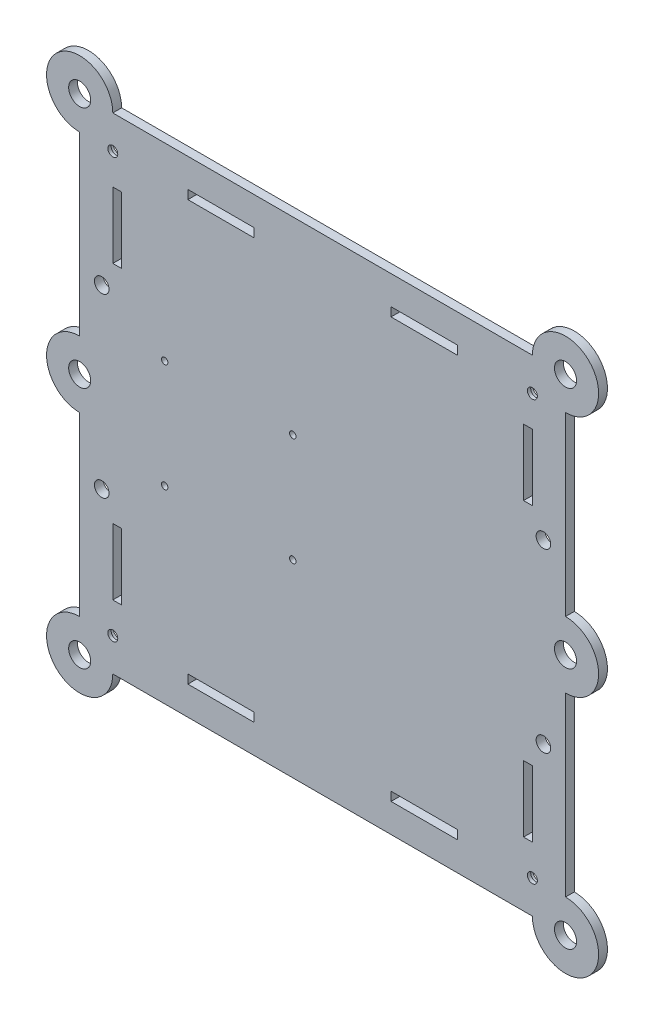
SolidWorks part; units mm, degrees
material "Aleación 6061"
ref_plane "Alzado" through (0, 0, 0) normal (0, 0, 1) x (1, 0, 0)
ref_plane "Planta" through (0, 0, 0) normal (0, 1, 0) x (1, 0, 0)
ref_plane "Vista lateral" through (0, 0, 0) normal (1, 0, 0) x (0, 0, -1)
sketch "Sk_Fondo" plane through (0, 0, 0) normal (0, 0, 1) x (1, 0, 0)
  line L0 (-110, 15) -> (-110, 95)
  line L1 (-95, -110) -> (95, -110)
  line L2 (-110, -95) -> (-110, -15)
  line L3 (-95, 110) -> (95, 110)
  line L4 (110, -95) -> (110, -15)
  line L5 (-110, -110) -> (110, 110) construction
  line L6 (-110, 110) -> (110, -110) construction
  line L7 (110, 15) -> (110, 95)
  arc A0 (-95, 110) -> (-110, 95) centre (-110, 110) ccw
  arc A1 (110, 95) -> (95, 110) centre (110, 110) ccw
  arc A2 (-110, -95) -> (-95, -110) centre (-110, -110) ccw
  arc A3 (95, -110) -> (110, -95) centre (110, -110) ccw
  arc A4 (-110, 15) -> (-110, -15) centre (-110, 0) ccw
  arc A5 (110, -15) -> (110, 15) centre (110, 0) ccw
  circle A6 centre (-110, 110) radius 5
  circle A7 centre (110, 110) radius 5
  circle A8 centre (110, 0) radius 5
  circle A9 centre (110, -110) radius 5
  circle A10 centre (-110, -110) radius 5
  circle A11 centre (-110, 0) radius 5
  point P0 (0, 0)
  dimension "D3" = 30
  dimension "D4" = 15
  dimension "D5" = 80
  dimension "D7" = 110
  dimension "D10" = 10
  dimension "D1" = 220
  dimension "D2" = 220
  dimension "D6" = 110
  dimension "D8" = 110
  dimension "D9" = 110
extrude "Fondo" add sketch "Sk_Fondo" along normal blind 4 from offset 54
sketch "Sk_Pasantes_M4_separadores" plane through (0, 0, 0) normal (0, 0, 1) x (1, 0, 0)
  circle A0 centre (-95, -95) radius 2.25
  circle A1 centre (-95, 95) radius 2.25
  circle A2 centre (95, -95) radius 2.25
  circle A3 centre (95, 95) radius 2.25
  dimension "D1" = 4.5
  dimension "D4" = 4.5
  dimension "D7" = 4.5
  dimension "D10" = 4.5
  dimension "D2" = 95
  dimension "D3" = 95
  dimension "D5" = 95
  dimension "D6" = 95
  dimension "D8" = 95
  dimension "D9" = 95
  dimension "D11" = 95
  dimension "D12" = 95
extrude "Pasantes_M4_separadores" cut sketch "Sk_Pasantes_M4_separadores" along normal blind 4 from offset 54
sketch "Sk_Avellanado_M4" plane through (0, 0, 0) normal (0, 0, 1) x (1, 0, 0)
  circle A0 centre (-95, -95) radius 4.2
  circle A1 centre (-95, 95) radius 4.2
  circle A2 centre (95, -95) radius 4.2
  circle A3 centre (95, 95) radius 4.2
  dimension "D1" = 8.4
  dimension "D4" = 8.4
  dimension "D7" = 8.4
  dimension "D10" = 8.4
  dimension "D2" = 95
  dimension "D3" = 95
  dimension "D5" = 95
  dimension "D6" = 95
  dimension "D8" = 95
  dimension "D9" = 95
  dimension "D11" = 95
  dimension "D12" = 95
extrude "Avellanado_M4" cut sketch "Sk_Avellanado_M4" along normal blind 2.5 from offset 54
sketch "Sk_Pasantes_M2-5_RPi" plane through (0, 0, 0) normal (0, 0, 1) x (1, 0, 0)
  circle A0 centre (-13.5, -24.5) radius 1.45
  circle A1 centre (-13.5, 24.5) radius 1.45
  circle A2 centre (-71.5, -24.5) radius 1.45
  circle A3 centre (-71.5, 24.5) radius 1.45
  dimension "D1" = 2.9
  dimension "D4" = 2.9
  dimension "D7" = 2.9
  dimension "D10" = 2.9
  dimension "D2" = 13.5
  dimension "D3" = 24.5
  dimension "D5" = 13.5
  dimension "D6" = 24.5
  dimension "D8" = 71.5
  dimension "D9" = 24.5
  dimension "D11" = 71.5
  dimension "D12" = 24.5
extrude "Pasantes_M2-5_RPi" cut sketch "Sk_Pasantes_M2-5_RPi" along normal blind 4 from offset 54
sketch "Sk_Avellanado_M2-5" plane through (0, 0, 0) normal (0, 0, 1) x (1, 0, 0)
  circle A0 centre (-13.5, -24.5) radius 2.5
  circle A1 centre (-13.5, 24.5) radius 2.5
  circle A2 centre (-71.5, -24.5) radius 2.5
  circle A3 centre (-71.5, 24.5) radius 2.5
  dimension "D1" = 5
  dimension "D4" = 5
  dimension "D7" = 5
  dimension "D10" = 5
  dimension "D2" = 13.5
  dimension "D3" = 24.5
  dimension "D5" = 13.5
  dimension "D6" = 24.5
  dimension "D8" = 71.5
  dimension "D9" = 24.5
  dimension "D11" = 71.5
  dimension "D12" = 24.5
extrude "Avellanado_M2-5" cut sketch "Sk_Avellanado_M2-5" along normal blind 1.5 from offset 54
sketch "Sk_Agujeros_anclaje" plane through (0, 0, 0) normal (0, 0, 1) x (1, 0, 0)
  circle A0 centre (-100, -40) radius 3.3
  circle A1 centre (-100, 40) radius 3.3
  circle A2 centre (100, -40) radius 3.3
  circle A3 centre (100, 40) radius 3.3
  dimension "D1" = 6.6
  dimension "D4" = 6.6
  dimension "D7" = 6.6
  dimension "D10" = 6.6
  dimension "D2" = 100
  dimension "D3" = 40
  dimension "D5" = 100
  dimension "D6" = 40
  dimension "D8" = 100
  dimension "D9" = 40
  dimension "D11" = 100
  dimension "D12" = 40
extrude "Agujeros_anclaje" cut sketch "Sk_Agujeros_anclaje" along normal blind 4 from offset 54
sketch "Croquis3" plane through (0, 0, -50) normal (0, 0, 1) x (1, 0, 0)
  line L0 (-91.5, -95) -> (91.5, -95) construction
  line L1 (-95, -110) -> (95, -110) construction
  line L2 (0, -110) -> (0, 110) construction
  line L3 (-61, -93) -> (-31, -93)
  line L4 (-61, -93) -> (-61, -97)
  line L5 (-61, -97) -> (-31, -97)
  line L6 (-31, -93) -> (-31, -97)
  line L7 (-61, -93) -> (-31, -97) construction
  line L8 (-61, -97) -> (-31, -93) construction
  line L9 (95, 110) -> (-95, 110) construction
  line L10 (-105, 0) -> (105, 0) construction
  line L11 (61, -93) -> (61, -97)
  line L12 (61, -93) -> (31, -93)
  line L13 (31, -93) -> (31, -97)
  line L14 (61, -97) -> (31, -97)
  line L15 (61, 93) -> (61, 97)
  line L16 (61, 97) -> (31, 97)
  line L17 (61, 93) -> (31, 93)
  line L18 (31, 93) -> (31, 97)
  line L19 (-61, 93) -> (-61, 97)
  line L20 (-61, 97) -> (-31, 97)
  line L21 (-31, 93) -> (-31, 97)
  line L22 (-61, 93) -> (-31, 93)
  line L23 (-93, 0) -> (-93, 90.96) construction
  line L24 (-95, -50.98) -> (-91, -50.98)
  line L25 (-95, 80.98) -> (-91, 80.98)
  line L26 (-95, 80.98) -> (-95, 50.98)
  line L27 (-95, 50.98) -> (-91, 50.98)
  line L28 (-91, 80.98) -> (-91, 50.98)
  line L29 (-95, 80.98) -> (-91, 50.98) construction
  line L30 (-95, 50.98) -> (-91, 80.98) construction
  line L31 (-91, -80.98) -> (-91, -50.98)
  line L32 (-95, -80.98) -> (-91, -80.98)
  line L33 (-95, -80.98) -> (-95, -50.98)
  line L34 (95, 80.98) -> (91, 80.98)
  line L35 (95, 50.98) -> (91, 50.98)
  line L36 (91, 80.98) -> (91, 50.98)
  line L37 (95, 80.98) -> (95, 50.98)
  line L38 (95, -50.98) -> (91, -50.98)
  line L39 (91, -80.98) -> (91, -50.98)
  line L40 (95, -80.98) -> (95, -50.98)
  line L41 (95, -80.98) -> (91, -80.98)
  circle A0 centre (-110, 0) radius 5 construction
  circle A1 centre (110, 0) radius 5 construction
  circle A3 centre (-100, 40) radius 3.3 construction
  point P2 (0, -95)
  point P6 (-46, -95)
  point P34 (-93, 40)
  point P37 (-93, 0)
  point P40 (-96.7, 40)
  point P41 (-93, 65.98)
  point P42 (-93, 65.98)
  dimension "D6" = 3.7
  dimension "D1" = 183
  dimension "D2" = 15
  dimension "D3" = 45.5
  dimension "D4" = 4
  dimension "D5" = 30
  dimension "D7" = 50.96
  dimension "D8" = 90.96
  dimension "D9" = 24.98
  dimension "D10" = 30
  dimension "D11" = 4
extrude "Cortar-Extruir1" cut sketch "Croquis3" against normal through all
